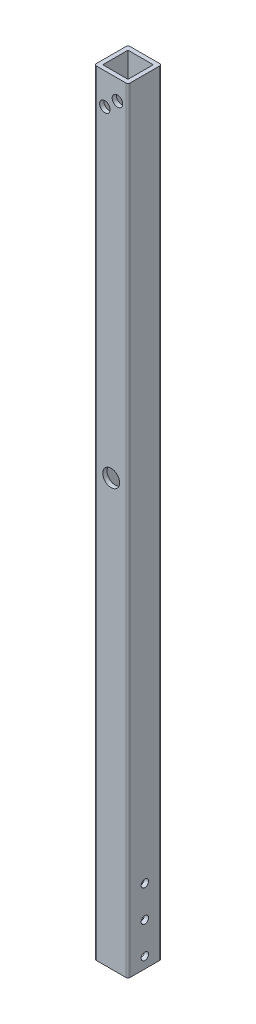
SolidWorks part; units mm, degrees
ref_plane "Front Plane" through (0, 0, 0) normal (0, 0, 1) x (1, 0, 0)
ref_plane "Top Plane" through (0, 0, 0) normal (0, 1, 0) x (1, 0, 0)
ref_plane "Right Plane" through (0, 0, 0) normal (1, 0, 0) x (0, 0, -1)
sketch "Sketch1" plane through (0, 0, 0) normal (0, 1, 0) x (1, 0, 0)
  line L0 (-5.2381, 2.8435) -> (-5.2381, -9.1565)
  line L1 (-7.2381, 4.8435) -> (8.7619, 4.8435)
  line L2 (-7.2381, 4.8435) -> (-7.2381, -11.1565)
  line L3 (-7.2381, -11.1565) -> (8.7619, -11.1565)
  line L4 (8.7619, 4.8435) -> (8.7619, -11.1565)
  line L5 (-5.2381, -9.1565) -> (6.7619, -9.1565)
  line L6 (6.7619, 2.8435) -> (6.7619, -9.1565)
  line L7 (-5.2381, 2.8435) -> (6.7619, 2.8435)
  dimension "D1" = 16
  dimension "D2" = 16
  dimension "D3" = 2
extrude "Boss-Extrude1" add sketch "Sketch1" along normal blind 368
fillet "Fillet1" radius 1 4 edges at (8.7619, 184, 11.1565) (-7.2381, 184, 11.1565) (-7.2381, 184, -4.8435) (8.7619, 184, -4.8435)
sketch "Sketch2" plane through (-7.2381, 0, 0) normal (-1, 0, 0) x (0, 0, 1)
  line L0 (-3.8435, 0) -> (10.1565, 0) construction
  line L2 (-4.8435, 0) -> (-4.8435, 368) construction
  line L3 (-4.8435, 368) -> (-4.8435, 0) construction
  circle A0 centre (3.1565, 5.25) radius 1.75
  circle A1 centre (3.1565, 20.25) radius 1.75
  circle A2 centre (3.1565, 35.25) radius 1.75
  dimension "D1" = 3.5
  dimension "D2" = 3.5
  dimension "D3" = 3.5
  dimension "D4" = 5.25
  dimension "D5" = 15
  dimension "D6" = 30
  dimension "D7" = 8
  dimension "D8" = 8
  dimension "D9" = 8
extrude "Cut-Extrude1" cut sketch "Sketch2" against normal blind 16
sketch "Sketch3" plane through (0, 0, -4.8435) normal (0, 0, -1) x (-1, 0, 0)
  line L0 (-8.7619, 0) -> (-8.7619, 368) construction
  line L1 (-7.7619, 0) -> (6.2381, 0) construction
  circle A0 centre (-0.7619, 202) radius 4
  dimension "D1" = 8
  dimension "D2" = 8
  dimension "D3" = 202
extrude "Cut-Extrude2" cut sketch "Sketch3" against normal blind 16
sketch "Sketch4" plane through (0, 0, 11.1565) normal (0, 0, 1) x (1, 0, 0)
  line L3 (-6.2381, 368) -> (7.7619, 368) construction
  circle A0 centre (-2.2322, 353.2527) radius 2.5
  circle A1 centre (3.7539, 358.5599) radius 2.5
  point P8 (0.7619, 368)
  dimension "D3" = 5
  dimension "D4" = 5
  dimension "D5" = 8
extrude "Cut-Extrude3" cut sketch "Sketch4" against normal blind 20
